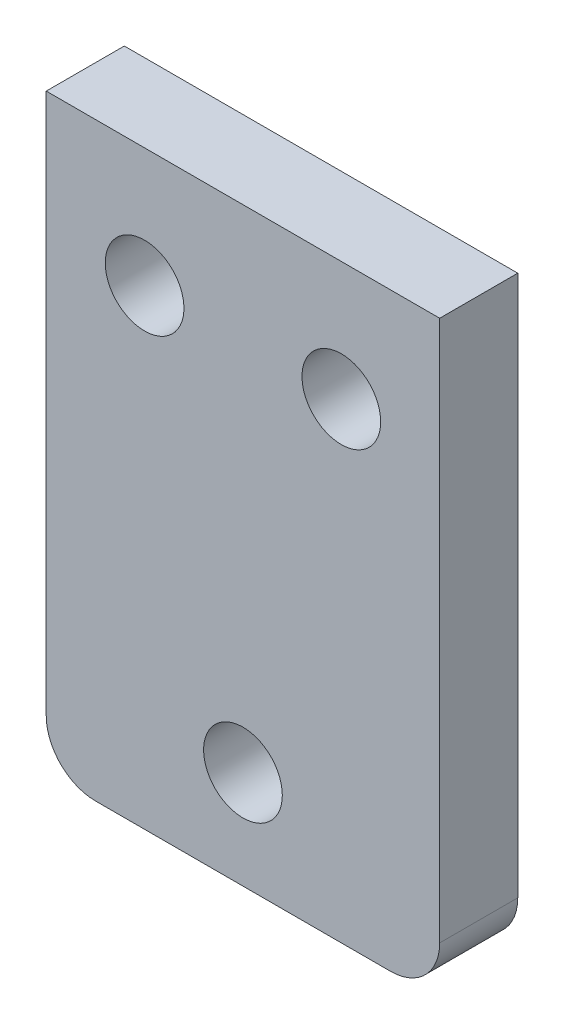
SolidWorks part; units mm, degrees
ref_plane "Front Plane" through (0, 0, 0) normal (0, 0, 1) x (1, 0, 0)
ref_plane "Top Plane" through (0, 0, 0) normal (0, 1, 0) x (1, 0, 0)
ref_plane "Right Plane" through (0, 0, 0) normal (1, 0, 0) x (0, 0, -1)
sketch "Sketch1" plane through (0, 0, 0) normal (0, 0, 1) x (1, 0, 0)
  line L0 (0, -26) -> (0, -50) construction
  line L1 (-8, -50) -> (8, -50)
  line L2 (-8, -50) -> (-8, -26)
  line L3 (-8, -26) -> (8, -26)
  line L4 (8, -50) -> (8, -26)
  line L5 (-8, -50) -> (8, -26) construction
  line L6 (-8, -26) -> (8, -50) construction
  circle A0 centre (4, -30.85) radius 1.6
  circle A1 centre (-4, -30.85) radius 1.6
  circle A26 centre (0, -46) radius 1.6
  dimension "D3" = 3.2
  dimension "D8" = 3.2
  dimension "D1" = 24
  dimension "D2" = 16
  dimension "D4" = 4
  dimension "D5" = 4.85
  dimension "D9" = 4
extrude "Boss-Extrude1" add sketch "Sketch1" along normal blind 3.175
fillet "Fillet1" radius 2 2 edges at (8, -50, 1.5875) (-8, -50, 1.5875)
